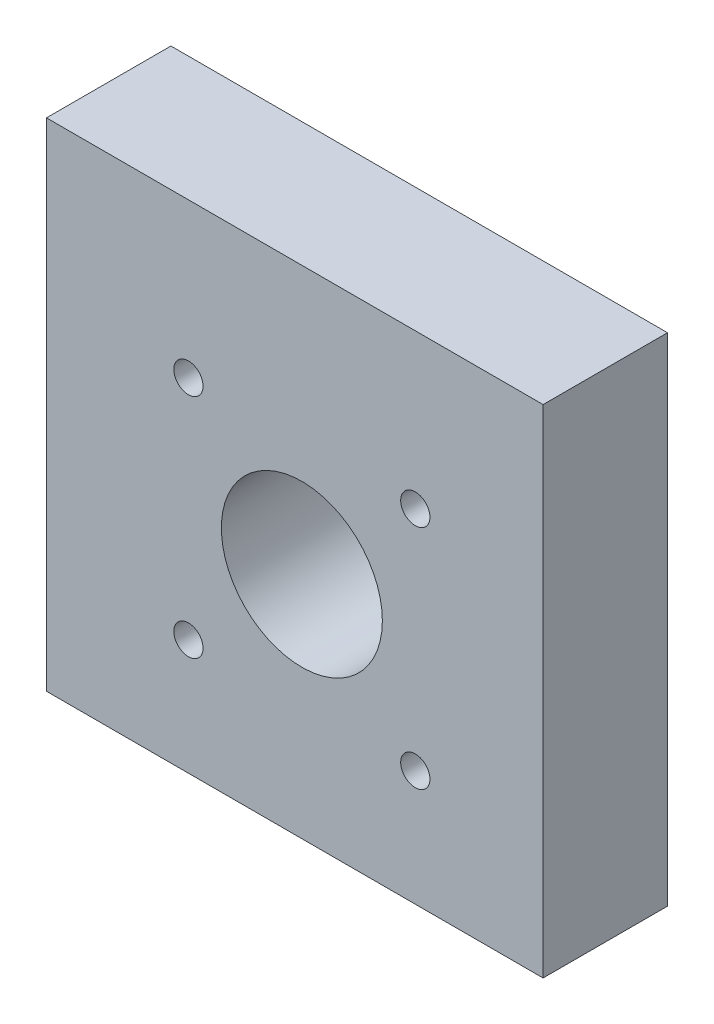
SolidWorks part; units mm, degrees
ref_plane "前视基准面" through (0, 0, 0) normal (0, 0, 1) x (1, 0, 0)
ref_plane "上视基准面" through (0, 0, 0) normal (0, 1, 0) x (1, 0, 0)
ref_plane "右视基准面" through (0, 0, 0) normal (1, 0, 0) x (0, 0, -1)
sketch "草图1" plane through (0, 0, 0) normal (0, 0, 1) x (1, 0, 0)
  line L0 (-34.893, 36.5634) -> (32.9597, 36.5634)
  line L1 (32.9597, 36.5634) -> (32.9597, -31.2893)
  line L2 (32.9597, -31.2893) -> (-34.893, -31.2893)
  line L3 (-34.893, -31.2893) -> (-34.893, 36.5634)
extrude "凸台-拉伸1" add sketch "草图1" against normal blind 17
sketch "草图2" plane through (0, 0, 0) normal (0, 0, 1) x (1, 0, 0)
  circle A0 centre (0, 0) radius 11
extrude "切除-拉伸1" cut sketch "草图2" against normal blind 17
sketch "草图3" plane through (0, 0, 0) normal (0, 0, 1) x (1, 0, 0)
  circle A0 centre (-15.5, 15.5) radius 2
  circle A1 centre (15.5, 15.5) radius 2
  circle A2 centre (-15.5, -15.5) radius 2
  circle A3 centre (15.5, -15.5) radius 2
extrude "切除-拉伸2" cut sketch "草图3" against normal blind 17
